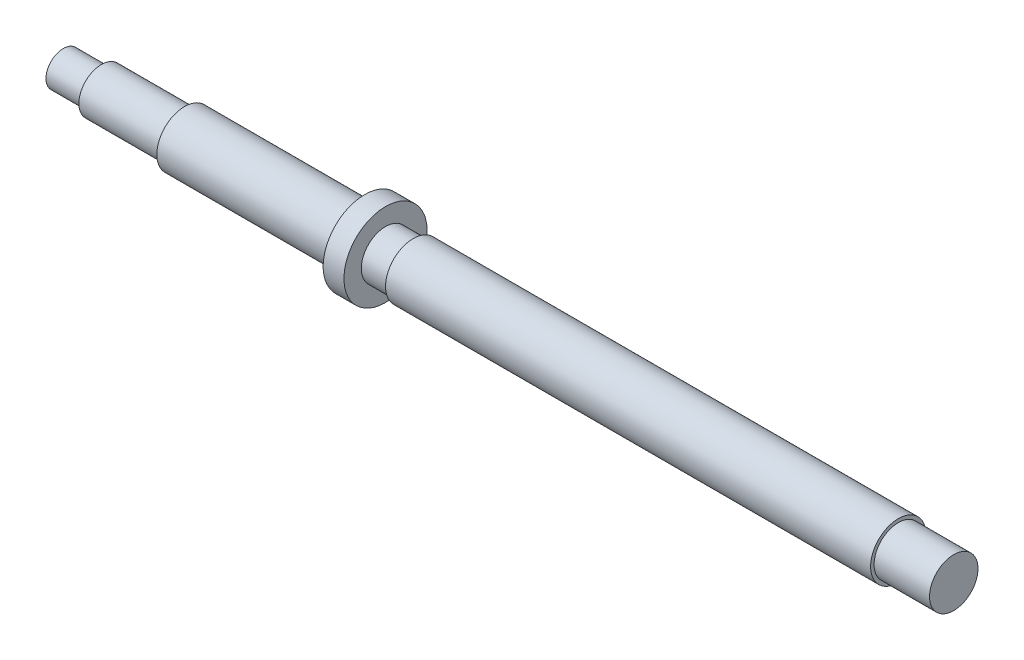
SolidWorks part; units mm, degrees
material "Gray Cast Iron (SN)"
ref_plane "Front Plane" through (0, 0, 0) normal (0, 0, 1) x (1, 0, 0)
ref_plane "Top Plane" through (0, 0, 0) normal (0, 1, 0) x (1, 0, 0)
ref_plane "Right Plane" through (0, 0, 0) normal (1, 0, 0) x (0, 0, -1)
sketch "Sketch1" plane through (0, 0, 0) normal (0, 0, 1) x (1, 0, 0)
  line L0 (-128.5, 0) -> (-128.5, 5)
  line L1 (-128.5, 5) -> (-117.5, 5)
  line L2 (-117.5, 5) -> (-117.5, 6.5)
  line L3 (-117.5, 6.5) -> (-93.5, 6.5)
  line L4 (-93.5, 6.5) -> (-93.5, 8)
  line L5 (-93.5, 8) -> (-41.5, 8)
  line L6 (-41.5, 8) -> (-41.5, 12)
  line L7 (-41.5, 12) -> (-35.5, 12)
  line L8 (-35.5, 12) -> (-35.5, 7)
  line L9 (-35.5, 7) -> (-27.5, 7)
  line L10 (-27.5, 7) -> (-27.5, 8)
  line L11 (-27.5, 8) -> (112.5, 8)
  line L12 (112.5, 8) -> (112.5, 7)
  line L13 (112.5, 7) -> (128.5, 7)
  line L14 (128.5, 7) -> (128.5, 0)
  line L15 (128.5, 0) -> (-128.5, 0)
  line L16 (0, 0) -> (0, 28.8685) construction
  point P2 (-117.5, 5.75)
  point P17 (-93.5, 7.25)
  dimension "D1" = 10
  dimension "D2" = 13
  dimension "D3" = 16
  dimension "D4" = 11
  dimension "D5" = 24
  dimension "D6" = 52
  dimension "D7" = 6
  dimension "D8" = 24
  dimension "D9" = 8
  dimension "D10" = 140
  dimension "D11" = 16
  dimension "D12" = 7
  dimension "D13" = 16
revolve "Revolve1" add sketch "Sketch1" angle 360 about L15
